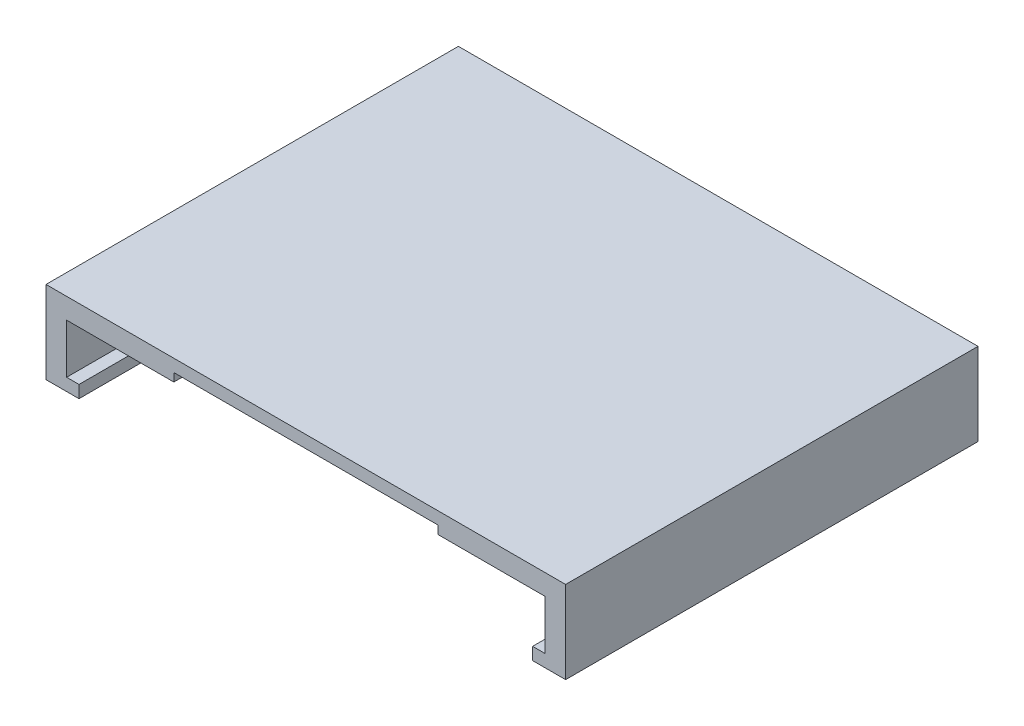
SolidWorks part; units mm, degrees
ref_plane "정면" through (0, 0, 0) normal (0, 0, 1) x (1, 0, 0)
ref_plane "윗면" through (0, 0, 0) normal (0, 1, 0) x (1, 0, 0)
ref_plane "우측면" through (0, 0, 0) normal (1, 0, 0) x (0, 0, -1)
sketch "스케치1" plane through (0, 0, 0) normal (0, 0, 1) x (1, 0, 0)
  line L2 (0, 0) -> (0, 10)
  line L3 (0, 10) -> (63, 10)
  line L4 (63, 0) -> (63, 10)
  line L6 (2.5, 1.5) -> (2.5, 7.5)
  line L7 (2.5, 7.5) -> (60.5, 7.5)
  line L8 (60.5, 1.5) -> (60.5, 7.5)
  line L13 (0, 0) -> (0, 1.5)
  line L14 (0, 0) -> (4, 0)
  line L15 (2.5, 1.5) -> (4, 1.5)
  line L16 (4, 0) -> (4, 1.5)
  line L17 (63, 0) -> (63, 3.5)
  line L18 (63, 0) -> (59, 0)
  line L19 (60.5, 1.5) -> (59, 1.5)
  line L20 (59, 0) -> (59, 1.5)
  line L21 (31.5, 10) -> (31.5, 7.5) construction
  line L27 (15.5, 8.5) -> (47.5, 8.5)
  line L28 (15.5, 8.5) -> (15.5, 7.5)
  line L29 (15.5, 7.5) -> (47.5, 7.5)
  line L30 (47.5, 8.5) -> (47.5, 7.5)
  line L31 (15.5, 8.5) -> (47.5, 7.5) construction
  line L32 (15.5, 7.5) -> (47.5, 8.5) construction
  point P5 (31.5, 8)
  point P22 (32.2539, 10.3336)
  point P23 (31.5, 9.5)
  dimension "D1" = 63
  dimension "D2" = 2.5
  dimension "D3" = 2.5
  dimension "D4" = 10
  dimension "D5" = 2.5
  dimension "D6" = 1.5
  dimension "D7" = 1.5
  dimension "D8" = 4
  dimension "D9" = 4
  dimension "D10" = 32
  dimension "D11" = 1
extrude "보스-돌출1" add sketch "스케치1" along normal blind 50 contours L20 L18 L4 L3 L2 L14 L16 L15 L6 L7 L28 L8 L19
